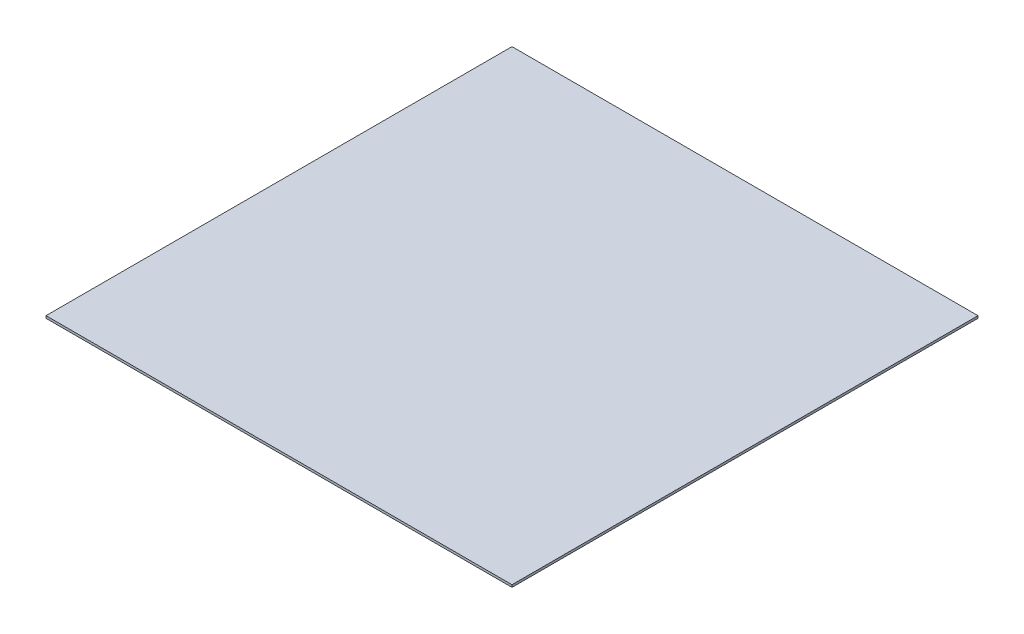
SolidWorks part; units mm, degrees
ref_plane "Front Plane" through (0, 0, 0) normal (0, 0, 1) x (1, 0, 0)
ref_plane "Top Plane" through (0, 0, 0) normal (0, 1, 0) x (1, 0, 0)
ref_plane "Right Plane" through (0, 0, 0) normal (1, 0, 0) x (0, 0, -1)
sketch "Sketch1" plane through (0, 0, 0) normal (0, 1, 0) x (1, 0, 0)
  line L1 (-1000, -1000) -> (1000, -1000)
  line L2 (-1000, -1000) -> (-1000, 1000)
  line L3 (-1000, 1000) -> (1000, 1000)
  line L4 (1000, -1000) -> (1000, 1000)
  line L5 (-1000, -1000) -> (1000, 1000) construction
  line L6 (-1000, 1000) -> (1000, -1000) construction
  point P0 (0, 0)
  dimension "D1" = 2000
  dimension "D2" = 2000
extrude "Boss-Extrude1" add sketch "Sketch1" along normal blind 10
